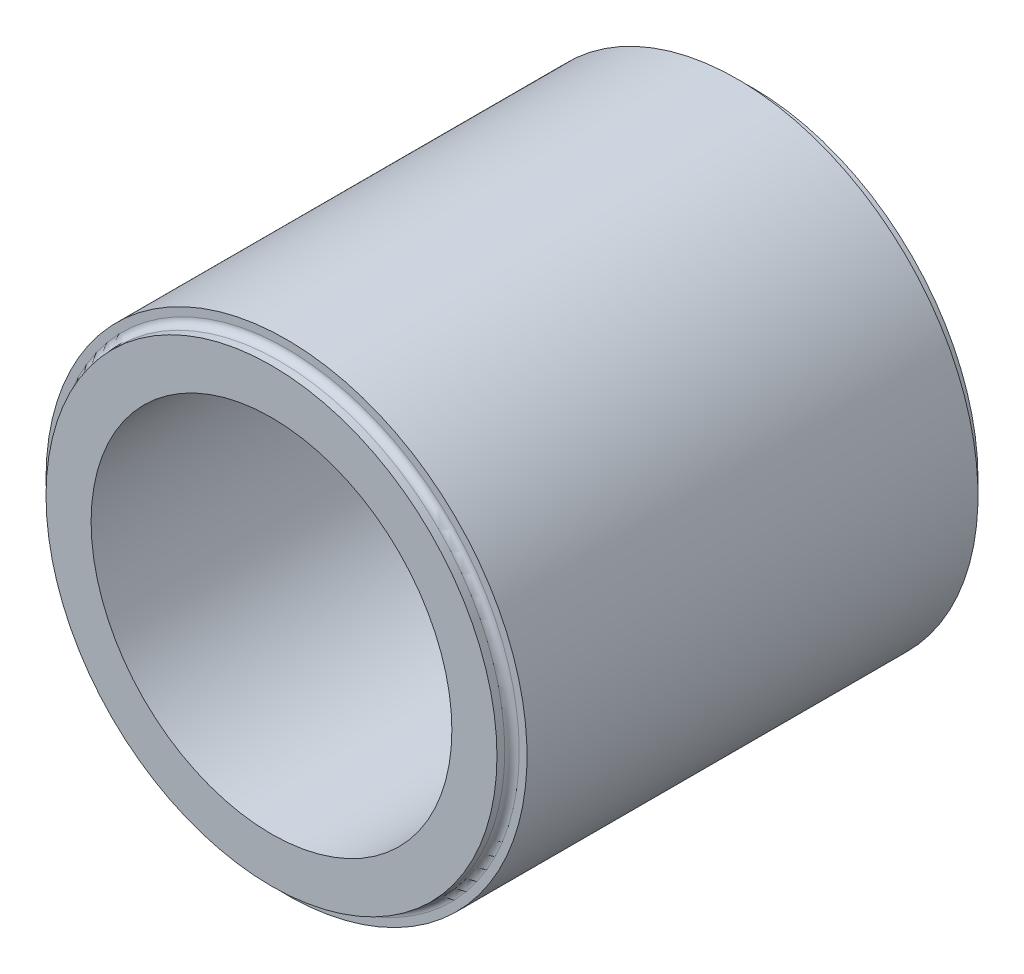
SolidWorks part; units mm, degrees
ref_plane "Front Plane" through (0, 0, 0) normal (0, 0, 1) x (1, 0, 0)
ref_plane "Top Plane" through (0, 0, 0) normal (0, 1, 0) x (1, 0, 0)
ref_plane "Right Plane" through (0, 0, 0) normal (1, 0, 0) x (0, 0, -1)
sketch "Sketch1" plane through (0, 0, 0) normal (0, 0, 1) x (1, 0, 0)
  circle A0 centre (0, 0) radius 19.05
  circle A1 centre (0, 0) radius 25.4
  dimension "D1" = 38.1
  dimension "D2" = 50.8
extrude "Boss-Extrude1" add sketch "Sketch1" along normal blind 50.8
sketch "Sketch2" plane through (0, 0, 0) normal (0, 1, 0) x (1, 0, 0)
  line L0 (0, -51.0808) -> (0, 0)
sketch "Sketch4" plane through (0, 0, 0) normal (0, 0, -1) x (-1, 0, 0)
  circle A0 centre (0, 0) radius 25.4
  circle A1 centre (0, 0) radius 23.8125
  dimension "D1" = 47.625
extrude "Cut-Extrude1" cut sketch "Sketch4" against normal blind 1.5875
ref_plane "Plane1" through (0, 0, 25.4) normal (0, 0, 1) x (1, 0, 0)
mirror "Mirror1" about plane through (0, 0, 25.4) normal (0, 0, 1) of "Cut-Extrude1"
fillet "Fillet1" radius 0.762 2 edges at (-23.8125, 0, 1.5875) (-23.8125, 0, 49.2125)
equation "\"D1@Sketch4\"=1+7/8"
